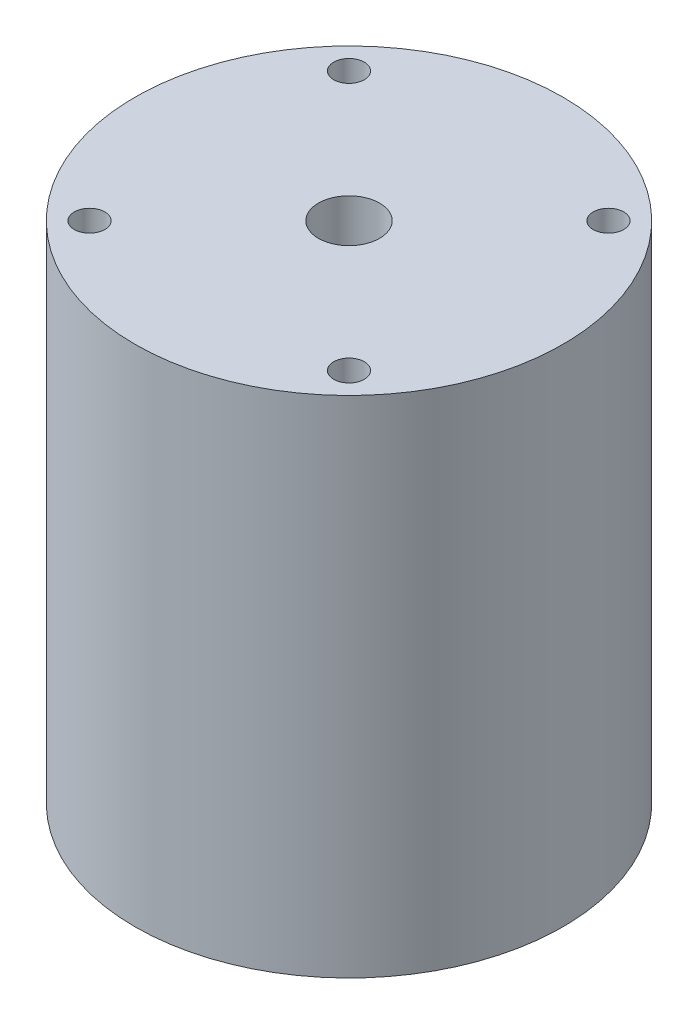
SolidWorks part; units mm, degrees
ref_plane "前视基准面" through (0, 0, 0) normal (0, 0, 1) x (1, 0, 0)
ref_plane "上视基准面" through (0, 0, 0) normal (0, 1, 0) x (1, 0, 0)
ref_plane "右视基准面" through (0, 0, 0) normal (1, 0, 0) x (0, 0, -1)
sketch "草图1" plane through (0, 0, 0) normal (0, 1, 0) x (1, 0, 0)
  circle A0 centre (0, 0) radius 28
extrude "凸台-拉伸1" add sketch "草图1" along normal blind 66
sketch "草图3" plane through (0, 66, 0) normal (0, 1, 0) x (1, 0, 0)
  line L0 (-16.9706, 16.9706) -> (0, 0)
  line L1 (0, 0) -> (0, 27.1996)
  circle A0 centre (0, 0) radius 24
  circle A1 centre (-16.9706, 16.9706) radius 2
  circle A2 centre (16.9706, 16.9706) radius 2
  circle A3 centre (16.9706, -16.9706) radius 2
  circle A4 centre (-16.9706, -16.9706) radius 2
  point P14 (0, 0)
  dimension "D1" = 4
  dimension "D2" = 45
hole_wizard "大小mm 暗销孔1" positions "3D草图1" profile "草图4" hole size "Ø4.0" standard "ANSI Metric"
sketch3d "3D草图1"
  point P0 (-16.9706, 66, -16.9706)
  point P3 (16.9706, 66, -16.9706)
  point P6 (16.9706, 66, 16.9706)
  point P9 (-16.9706, 66, 16.9706)
sketch "草图4" plane through (-16.9706, 66, -16.9706) normal (1, 0, 0) x (0, 0, 1)
  line L0 (0, 0) -> (0, 16.2017)
  line L1 (0, 16.2017) -> (2, 15)
  line L2 (2, 15) -> (2, 0)
  line L5 (2, 0) -> (0, 0)
  line L10 (0, 16.2017) -> (-2, 15) construction
  line L11 (0, -6.35) -> (0, 107.95) construction
  dimension "孔直径" = 4
  dimension "孔深度" = 15
  dimension "导头角度" = 118
sketch "草图5" plane through (0, 66, 0) normal (0, 1, 0) x (1, 0, 0)
  circle A0 centre (0, 0) radius 4
extrude "切除-拉伸1" cut sketch "草图5" against normal through all
sketch "草图6" plane through (0, 0, 0) normal (0, -1, 0) x (1, 0, 0)
  line L0 (-8.5, -20.5) -> (-8.5, 20.5)
  line L1 (-8.5, -20.5) -> (8.5, -20.5)
  line L2 (-8.5, 20.5) -> (8.5, 20.5)
  line L3 (8.5, -20.5) -> (8.5, 20.5)
  line L4 (-8.5, -20.5) -> (8.5, 20.5) construction
  line L5 (-8.5, 20.5) -> (8.5, -20.5) construction
  point P1 (0, 0)
  dimension "D1" = 41
  dimension "D2" = 17
hole_wizard "大小mm 暗销孔2" positions "3D草图2" profile "草图7" hole size "Ø4.0" standard "ANSI Metric"
sketch3d "3D草图2"
  point P0 (-8.5, 0, 20.5)
  point P3 (8.5, 0, 20.5)
  point P6 (8.5, 0, -20.5)
  point P9 (-8.5, 0, -20.5)
sketch "草图7" plane through (-8.5, 0, 20.5) normal (1, 0, 0) x (0, 0, -1)
  line L0 (0, 0) -> (0, 16.2017)
  line L1 (0, 16.2017) -> (2, 15)
  line L2 (2, 15) -> (2, 0)
  line L5 (2, 0) -> (0, 0)
  line L10 (0, 16.2017) -> (-2, 15) construction
  line L11 (0, -6.35) -> (0, 107.95) construction
  dimension "孔直径" = 4
  dimension "孔深度" = 15
  dimension "导头角度" = 118
